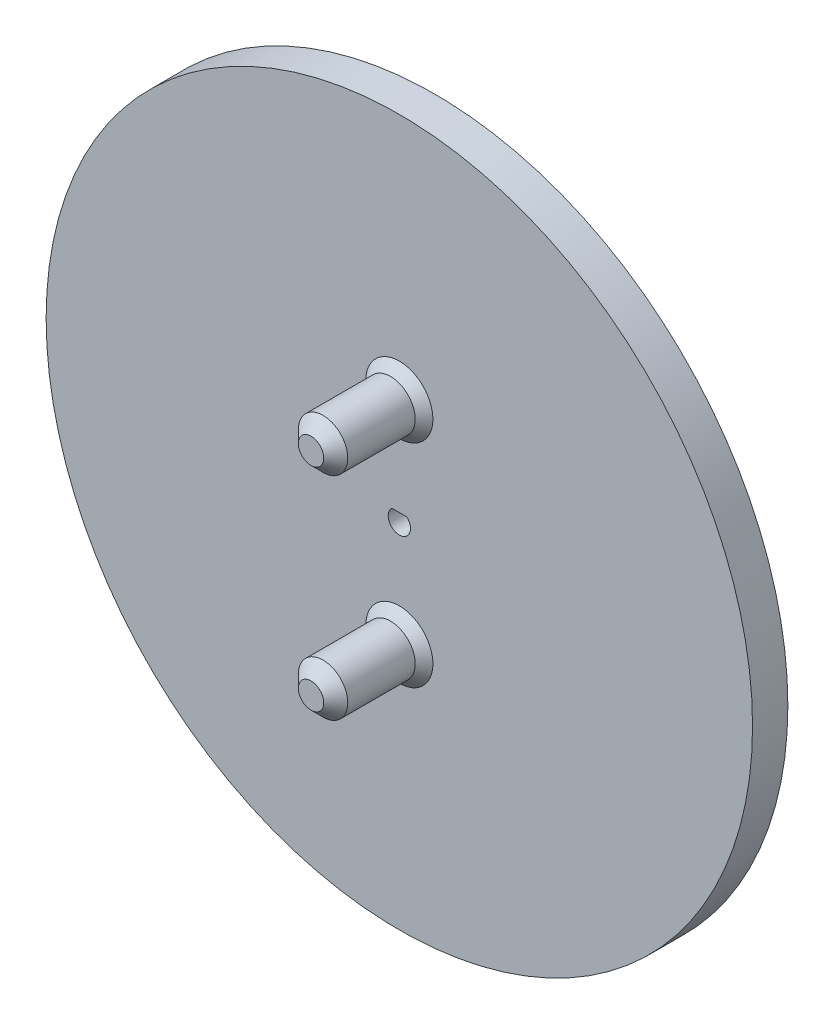
SolidWorks part; units mm, degrees
ref_plane "Front Plane" through (0, 0, 0) normal (0, 0, 1) x (1, 0, 0)
ref_plane "Top Plane" through (0, 0, 0) normal (0, 1, 0) x (1, 0, 0)
ref_plane "Right Plane" through (0, 0, 0) normal (1, 0, 0) x (0, 0, -1)
sketch "Sketch1" plane through (0, 0, 0) normal (0, 0, 1) x (1, 0, 0)
  circle A0 centre (0, 0) radius 63.5
  dimension "D1" = 127
extrude "Boss-Extrude1" add sketch "Sketch1" along normal blind 6.35
sketch "Sketch3" plane through (0, 0, 6.35) normal (0, 0, 1) x (1, 0, 0)
  line L0 (-1.3229, 1.5) -> (1.3229, 1.5)
  line L1 (0, -2) -> (4.1971, -2) construction
  arc A0 (-1.3229, 1.5) -> (1.3229, 1.5) centre (0, 0) ccw
  point P1 (0, 0)
  point P6 (0, 1.5)
  dimension "D1" = 4
  dimension "D2" = 3.5
extrude "Cut-Extrude1" cut sketch "Sketch3" against normal through all
sketch "Sketch4" plane through (0, 0, 6.35) normal (0, 0, 1) x (1, 0, 0)
  line L0 (0, 0) -> (0, 19.05) construction
  circle A0 centre (0, 19.05) radius 4.445
  dimension "D2" = 8.89
  dimension "D1" = 19.05
extrude "Boss-Extrude2" add sketch "Sketch4" along normal blind 15.875
mirror "Mirror3" about plane through (0, 0, 0) normal (0, 1, 0) of "Boss-Extrude2"
chamfer "Chamfer2" distance 2.159 angle 45 2 edges at (4.445, -19.05, 22.225) (4.445, 19.05, 22.225)
chamfer "Chamfer3" distance 1.5875 angle 45 2 edges at (4.445, -19.05, 6.35) (4.445, 19.05, 6.35)
